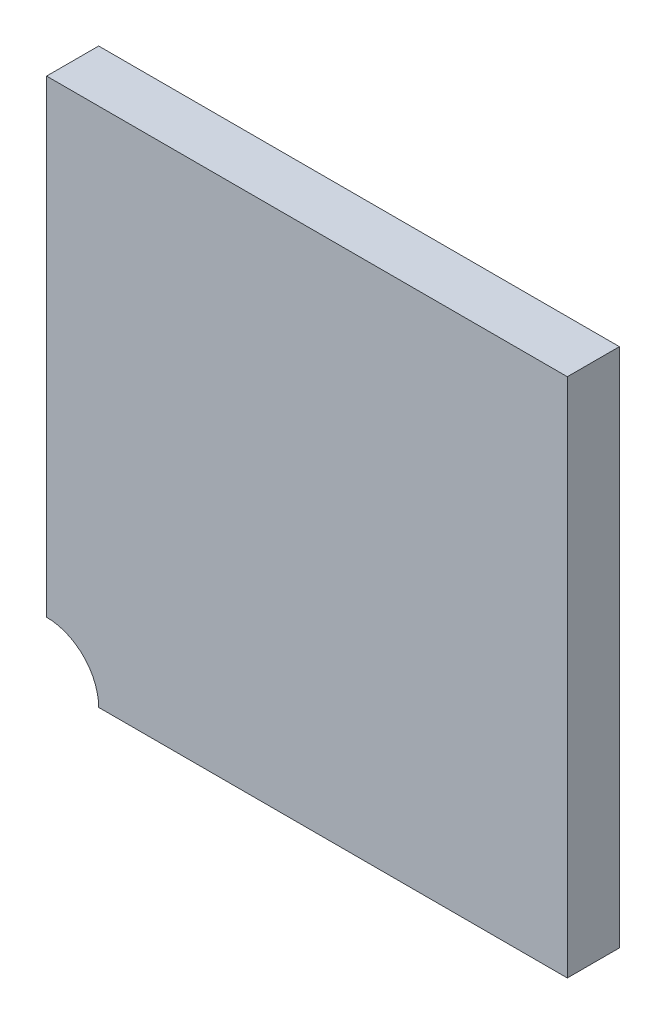
SolidWorks part; units mm, degrees
ref_plane "Plane1" through (0, 0, 0) normal (0, 0, 1) x (1, 0, 0)
ref_plane "Plane2" through (0, 0, 0) normal (0, 1, 0) x (1, 0, 0)
ref_plane "Plane3" through (0, 0, 0) normal (1, 0, 0) x (0, 0, -1)
other "Configuration Table"
sketch "Sketch1" plane through (0, 0, 0) normal (0, 0, 1) x (1, 0, 0)
  line L0 (-25.4, -152.4) -> (-25.4, 76.2)
  line L1 (-25.4, 76.2) -> (228.6, 76.2)
  line L2 (228.6, 76.2) -> (228.6, -177.8)
  line L3 (228.6, -177.8) -> (0, -177.8)
  arc A0 (-25.4, -152.4) -> (0, -177.8) centre (-25.4, -177.8) cw
  dimension "D4" = 25.4
  dimension "D1" = 254
  dimension "D2" = 254
  dimension "D3" = 228.6
extrude "Base-Extrude" add sketch "Sketch1" along normal blind 25.4
